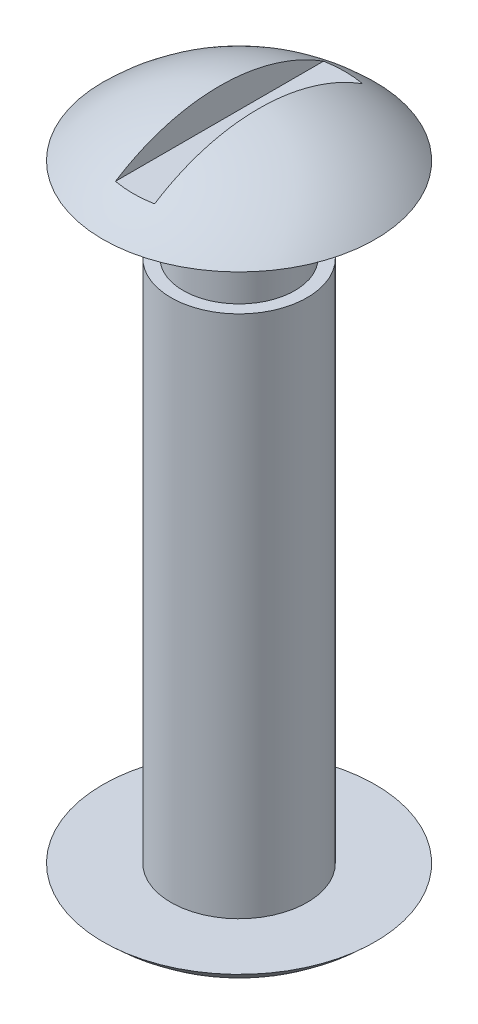
SolidWorks part; units mm, degrees
material "6063-T6"
ref_plane "Front Plane" through (0, 0, 0) normal (0, 0, 1) x (1, 0, 0)
ref_plane "Top Plane" through (0, 0, 0) normal (0, 1, 0) x (1, 0, 0)
ref_plane "Right Plane" through (0, 0, 0) normal (1, 0, 0) x (0, 0, -1)
sketch "Sketch1" plane through (0, 0, 0) normal (0, 0, 1) x (1, 0, 0)
  line L0 (0, 22.1234) -> (0, 0) construction
  line L1 (0, 22.1234) -> (4.953, 22.1234) construction
  line L2 (0, 0) -> (4.953, 0) construction
  line L3 (4.953, 22.1234) -> (2.032, 22.1234)
  line L4 (2.4765, 0) -> (2.4765, 19.05)
  line L5 (2.4765, 0) -> (4.953, 0)
  line L6 (0, 24.1554) -> (0, -2.032)
  line L7 (2.4765, 19.05) -> (2.032, 19.05)
  line L8 (2.032, 19.05) -> (2.032, 22.1234)
  line L9 (4.953, 22.1234) -> (4.953, 19.05) construction
  line L10 (0, -2.032) -> (0, 0) construction
  line L11 (0, 22.1234) -> (0, 24.1554) construction
  line L12 (0, 22.1234) -> (0, 24.1554) construction
  arc A0 (0, 24.1554) -> (4.953, 22.1234) centre (0, 17.1029) cw
  arc A1 (0, -2.032) -> (4.953, 0) centre (0, 5.0205) ccw
  dimension "D1" = 2.4765
  dimension "D2" = 2.032
  dimension "D3" = 19.05
  dimension "D4" = 3.0734
  dimension "D5" = 19.05
  dimension "D6" = 2.032
revolve "Revolve1" add sketch "Sketch1" angle 360 about L6
sketch "Sketch2" plane through (0, 0, 0) normal (0, 0, 1) x (1, 0, 0)
  line L0 (0, 23.0124) -> (0, 0) construction
  line L1 (-0.7112, 24.2824) -> (0.7112, 24.2824)
  line L2 (-0.7112, 24.2824) -> (-0.7112, 23.0124)
  line L3 (-0.7112, 23.0124) -> (0.7112, 23.0124)
  line L4 (0.7112, 24.2824) -> (0.7112, 23.0124)
  line L5 (-2.032, 22.1234) -> (2.032, 22.1234) construction
  dimension "D1" = 1.4224
  dimension "D2" = 0.889
  dimension "D3" = 1.27
extrude "Cut-Extrude1" cut sketch "Sketch2" against normal through all both and the other way through all
equation "\"Height\"= 28in"
equation "\"Width\"= 28in"
equation "\"Depth\"= 20in"
equation "\"Plexi\"= .121in"
equation "\"MagnetThickness\"=3mm"
equation "\"MagnetDiameter\"=12mm"
equation "\"DoorPlexi\"= \"Plexi\""
equation "\"BasePlateThickness\"= 0.5in"
equation "\"BasePlateWidth\"= \"Width\"+8in-\"Plexi\""
equation "\"BasePlateDepth\"= \"Depth\"-\"Plexi\"-\"DoorPlexi\""
equation "\"Boxsize\"= .75in"
equation "\"Boxinner\"= .625in"
equation "\"CornerCube\"= 0.75in"
equation "\"FingerLength\"= 1.125in"
equation "\"FingerWidth\"= .625in"
equation "\"Cutwidth\"= .016in"
equation "\"Earsize\"= 1in + \"Cutwidth\" /2"
equation "\"Slotsize\"= 1in - \"Cutwidth\" / 2"
equation "\"InnerWidth\"= \"Width\" - 2* \"Plexi\""
equation "\"InnerHeight\"= \"Height\" -2 * \"Plexi\""
equation "\"InnerDepth\"= \"Depth\" - 2*\"Plexi\""
equation "\"RearNumHoles\"= 7"
equation "\"RearHolesBorder\"= 2.2"
equation "\"RearHoleSpacing\"= (\"Width\" - 2*\"RearHolesBorder\") / (\"RearNumHoles\"-1)"
equation "\"RearBarLength\"= (\"InnerWidth\"-2*\"CornerCube\")"
equation "\"RearTopNumHoles\"= 6"
equation "\"RearTopHolesBorder\"= 2.5"
equation "\"RearTopHolesSpacing\"= (\"Width\" - 2*\"RearTopHolesBorder\") / (\"RearTopNumHoles\"-1)"
equation "\"SideTopNumHoles\"= 5"
equation "\"SideTopHoleOffset\"=\"CornerCube\"+\"FingerLength\"+\"Plexi\"+.5"
equation "\"SideTopHoleSpacing\"= (\"TopBarDepth\"-2*\"SideTopHoleOffset\") / (\"SideTopNumHoles\"-1)"
equation "\"SideHorizNumHoles\"= 6"
equation "\"SideHorizHoleBorder\"= 2.25"
equation "\"SideHorizHoleSpacing\"= (\"TopBarDepth\"-2*\"SideHorizHoleBorder\") / (\"SideHorizNumHoles\"-1)"
equation "\"SideVertBarLength\"=\"Height\"-\"BasePlateThickness\"-2*\"CornerCube\"-\"Plexi\""
equation "\"SideVertNumHoles\"= 6"
equation "\"SideVertHolesBorder\"= \"CornerCube\"+\"FingerLength\"+.9"
equation "\"SideVertHoleSpacing\"= (\"InnerHeight\" - 2*\"SideVertHolesBorder\") / (\"SideVertNumHoles\"-1)"
equation "\"RearSideVertNumHoles\"= 7"
equation "\"RearSideVertHolesBorder\"= 2.5"
equation "\"RearSideVertHoleSpacing\"= (\"InnerHeight\" - 2*\"RearSideVertHolesBorder\") / (\"RearSideVertNumHoles\"-1)"
equation "\"RivetDia\"= .228in"
equation "\"SlotDepth\"= \"Plexi\" + 0.75in + .005in"
equation "\"SideSlotWidth\"= \"Plexi\"+.005in"
equation "\"SidePanelVertSpacing\"= (\"Height\"-2*(1.75-\"Plexi\")) / 5"
equation "\"BottomPanelSideHoleSpacing\"= (\"InnerDepth\"-2*(1.75-\"Plexi\")) / 4"
equation "\"FrontDoorGap\"= .1in"
equation "\"TopDepth\"= \"Depth\"-\"DoorPlexi\"-\"FrontDoorGap\""
equation "\"TopBarDepth\"= \"Depth\"-\"DoorPlexi\"-\"Plexi\"-2*\"MagnetThickness\"-2*\"CornerCube\""
equation "\"D4@Sketch1\"=\"Plexi\""
equation "\"D5@Sketch1\"=\"Boxsize\""
